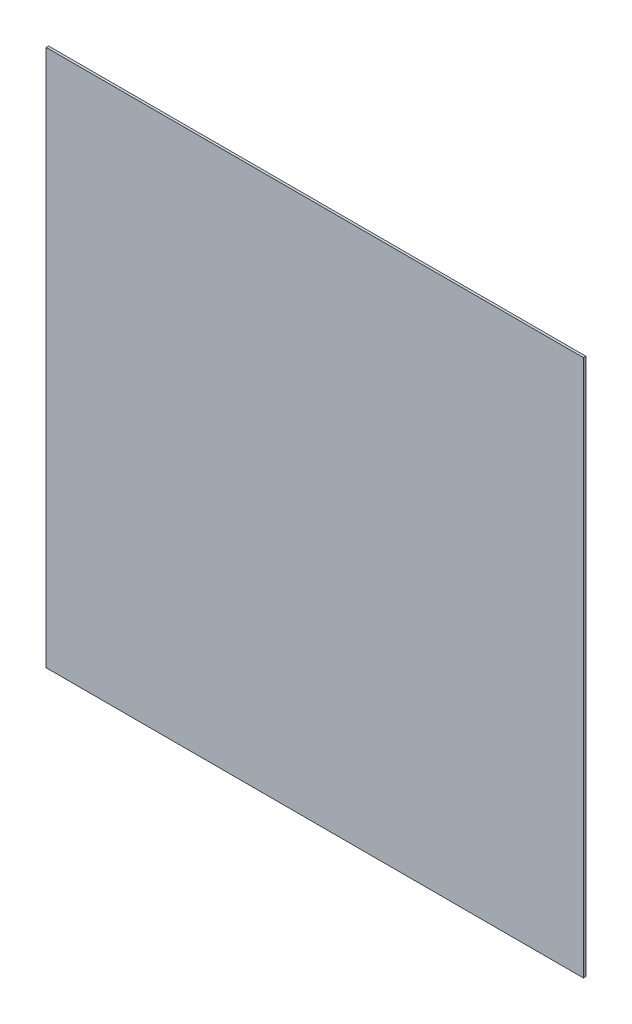
SolidWorks part; units mm, degrees
ref_plane "Front Plane" through (0, 0, 0) normal (0, 0, 1) x (1, 0, 0)
ref_plane "Top Plane" through (0, 0, 0) normal (0, 1, 0) x (1, 0, 0)
ref_plane "Right Plane" through (0, 0, 0) normal (1, 0, 0) x (0, 0, -1)
sketch "Sketch1" plane through (0, 0, 0) normal (0, 0, 1) x (1, 0, 0)
  line L1 (-11000, -11000) -> (11000, -11000)
  line L2 (-11000, -11000) -> (-11000, 11000)
  line L3 (-11000, 11000) -> (11000, 11000)
  line L4 (11000, -11000) -> (11000, 11000)
  line L5 (-11000, -11000) -> (11000, 11000) construction
  line L6 (-11000, 11000) -> (11000, -11000) construction
  point P0 (0, 0)
  dimension "D1" = 22000
  dimension "D2" = 22000
extrude "Boss-Extrude1" add sketch "Sketch1" along normal blind 100
